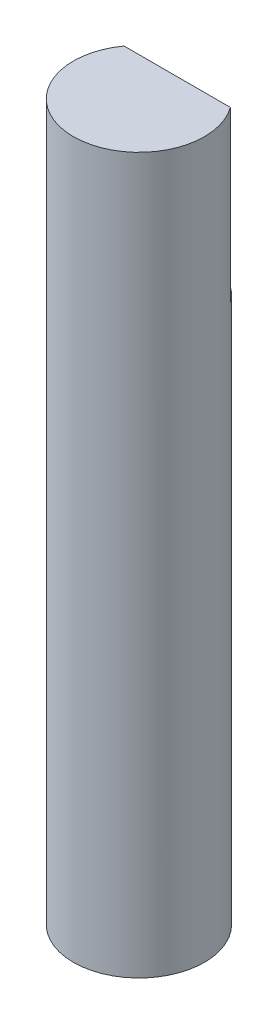
SolidWorks part; units mm, degrees
ref_plane "Front Plane" through (0, 0, 0) normal (0, 0, 1) x (1, 0, 0)
ref_plane "Top Plane" through (0, 0, 0) normal (0, 1, 0) x (1, 0, 0)
ref_plane "Right Plane" through (0, 0, 0) normal (1, 0, 0) x (0, 0, -1)
sketch "Sketch1" plane through (0, 0, 0) normal (0, 1, 0) x (1, 0, 0)
  circle A0 centre (0, 0) radius 3.85
  dimension "D1" = 7.7
extrude "Boss-Extrude1" add sketch "Sketch1" along normal blind 42 contours A0
ref_plane "Plane1" through (0, 42, 0) normal (0, 1, 0) x (1, 0, 0)
sketch "Sketch2" plane through (0, 42, 0) normal (0, 1, 0) x (1, 0, 0)
  line L0 (-3.85, 0) -> (3.85, 0) construction
  line L1 (-3.1241, 2.25) -> (3.1241, 2.25)
  circle A0 centre (0, 0) radius 3.85 construction
  arc A2 (3.1241, 2.25) -> (-3.1241, 2.25) centre (0, 0) ccw
  point P7 (0, 0)
  dimension "D1" = 2.25
extrude "Cut-Extrude1" cut sketch "Sketch2" against normal blind 10 contours L1 A2
